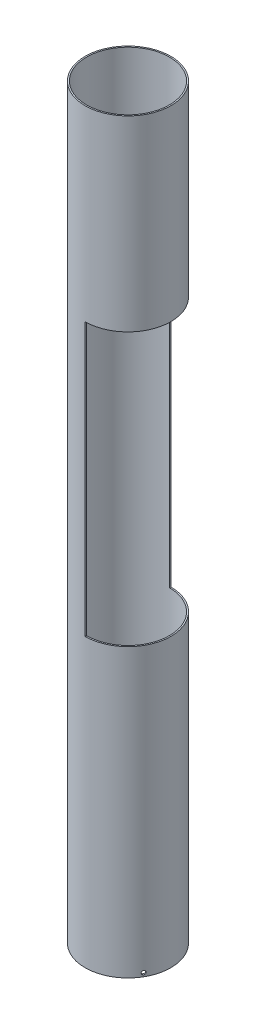
SolidWorks part; units mm, degrees
ref_plane "Front Plane" through (0, 0, 0) normal (0, 0, 1) x (1, 0, 0)
ref_plane "Top Plane" through (0, 0, 0) normal (0, 1, 0) x (1, 0, 0)
ref_plane "Right Plane" through (0, 0, 0) normal (1, 0, 0) x (0, 0, -1)
sketch "Sketch1" plane through (0, 0, 0) normal (0, 1, 0) x (1, 0, 0)
  circle A0 centre (0, 0) radius 38.1
  circle A3 centre (0, 0) radius 39.37
extrude "Boss-Extrude1" add sketch "Sketch1" along normal blind 685.8
sketch "Sketch2" plane through (0, 0, 0) normal (0, 0, 1) x (1, 0, 0)
  circle A0 centre (0, 3.2871) radius 1.6929
extrude "Cut-Extrude1" cut sketch "Sketch2" against normal blind 61.4
pattern_circular "CirPattern3" count 3 over 360 of "Cut-Extrude1"
sketch "Sketch3" plane through (0, 0, 0) normal (1, 0, 0) x (0, 0, -1)
  line L0 (-39.37, 665.4) -> (-39.37, 0) construction
  line L1 (-39.37, 513.9904) -> (39.37, 513.9904)
  line L2 (-39.37, 513.9904) -> (-39.37, 282.655)
  line L4 (39.37, 513.9904) -> (39.37, 282.655)
  line L5 (39.37, 4.98) -> (39.37, 665.4) construction
  line L6 (-39.37, 282.655) -> (-39.37, 276.305)
  line L7 (-39.37, 665.4) -> (-39.37, 0) construction
  line L8 (-39.37, 276.305) -> (-39.37, 269.955)
  line L10 (39.37, 4.98) -> (39.37, 665.4) construction
  line L11 (39.37, 269.955) -> (39.37, 282.655)
  line L12 (-39.37, 269.955) -> (-39.37, 263.605)
  line L13 (-39.37, 263.605) -> (39.37, 263.605)
  line L14 (39.37, 263.605) -> (39.37, 269.955)
extrude "Cut-Extrude2" cut sketch "Sketch3" along normal blind 72.4
